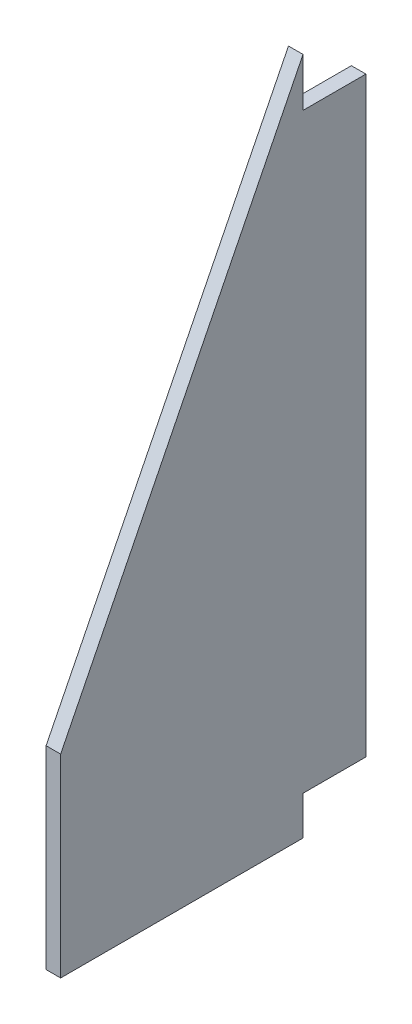
SolidWorks part; units mm, degrees
material "Beech"
ref_plane "Front Plane" through (0, 0, 0) normal (0, 0, 1) x (1, 0, 0)
ref_plane "Top Plane" through (0, 0, 0) normal (0, 1, 0) x (1, 0, 0)
ref_plane "Right Plane" through (0, 0, 0) normal (1, 0, 0) x (0, 0, -1)
sketch "Sketch1" plane through (0, 0, 0) normal (1, 0, 0) x (0, 0, -1)
  line L0 (-33.9725, 0) -> (-83.9725, 0)
  line L1 (-83.9725, 0) -> (-83.9725, 40)
  line L2 (-83.9725, 40) -> (-33.9725, 140)
  line L3 (-33.9725, 140) -> (-33.9725, 130)
  line L4 (-33.9725, 8) -> (-21, 8)
  line L5 (-21, 8) -> (-21, 130)
  line L6 (-21, 130) -> (-33.9725, 130)
  line L7 (-33.9725, 8) -> (-33.9725, 0)
  dimension "D1" = 50
  dimension "D2" = 100
  dimension "D3" = 140
  dimension "D4" = 33.9725
  dimension "D5" = 21
  dimension "D6" = 8
  dimension "D7" = 10
extrude "Boss-Extrude1" add sketch "Sketch1" along normal mid plane 3
